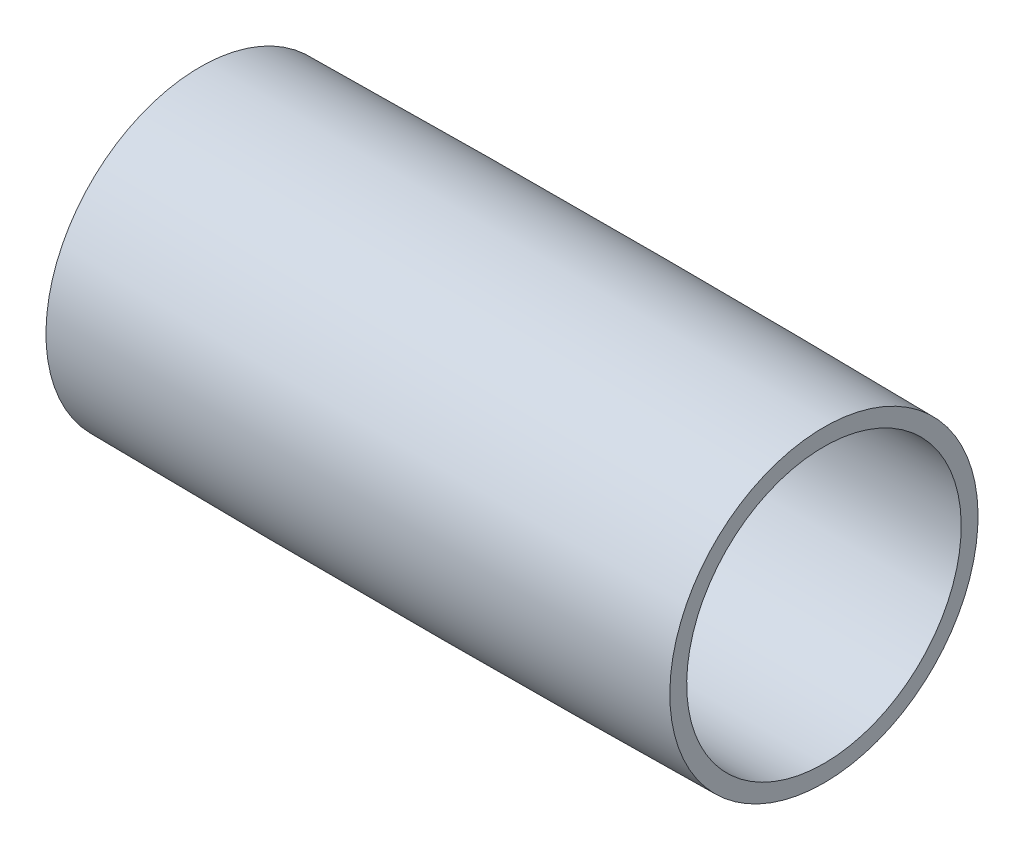
SolidWorks part; units mm, degrees
ref_plane "Front Plane" through (0, 0, 0) normal (0, 0, 1) x (1, 0, 0)
ref_plane "Top Plane" through (0, 0, 0) normal (0, 1, 0) x (1, 0, 0)
ref_plane "Right Plane" through (0, 0, 0) normal (1, 0, 0) x (0, 0, -1)
sketch "Sketch1" plane through (0, 0, 0) normal (0, 0, 1) x (1, 0, 0)
  line L0 (0, 0) -> (100, 0) construction
  line L2 (0, 25) -> (100, 25)
  line L3 (0, 25) -> (0, 22)
  line L4 (0, 22) -> (100, 22)
  line L5 (100, 25) -> (100, 22)
  dimension "L" = 100
  dimension "D" = 50
  dimension "D1" = 3
revolve "Revolve1" add sketch "Sketch1" angle 360 about L0
sketch "Sketch2" plane through (0, 0, 0) normal (0, 0, 1) x (1, 0, 0)
  line L0 (100, 25) -> (100, 22) construction
  line L1 (0, 25) -> (100, 25) construction
  line L2 (0, 25) -> (0, 24.7)
  line L3 (0, 25) -> (0, 22) construction
  line L4 (100, 25) -> (100, 24.7)
  line L5 (0, 24.7) -> (100, 24.7) construction
  line L6 (0, 25) -> (0, 25.3)
  line L7 (0, 25.3) -> (100, 25.3)
  line L8 (100, 25.3) -> (100, 25)
  arc A0 (0, 24.7) -> (100, 24.7) centre (50, -4141.8167) cw
  dimension "D1" = 0.3
revolve "Cut-Revolve1" cut sketch "Sketch2" angle 360 about L0
ref_plane "Plane1" [suppressed] through (0, 10, 0) normal (0, 1, 0) x (1, 0, 0)
hole_wizard "Diameter Hole1" [suppressed] positions "Sketch4" profile "Sketch3" hole size "Ø4.0" standard "JIS"
sketch "Sketch4" [suppressed] plane through (0, 10, 0) normal (0, 1, 0) x (1, 0, 0)
  line L0 (0, 0) -> (15, 0) construction
  point P0 (7.5, 0)
  dimension "D1" = 50
sketch "Sketch3" [suppressed] plane through (7.5, 10, 0) normal (1, 0, 0) x (0, 0, 1)
  line L0 (0, 0) -> (0, 20)
  line L1 (0, 20) -> (2, 20)
  line L2 (2, 20) -> (2, 0)
  line L5 (2, 0) -> (0, 0)
  line L11 (0, 0) -> (0, 20) construction
  dimension "MSM_1" = 4
  dimension "Thru Hole Depth" = 20
pattern_circular "CirPattern1" [suppressed] count 2 over 90
equation "\"Plane dim\"= \"D@Sketch1\" * 0.5"
equation "\"D1@Sketch4\"=\"L@Sketch1\"/2"
